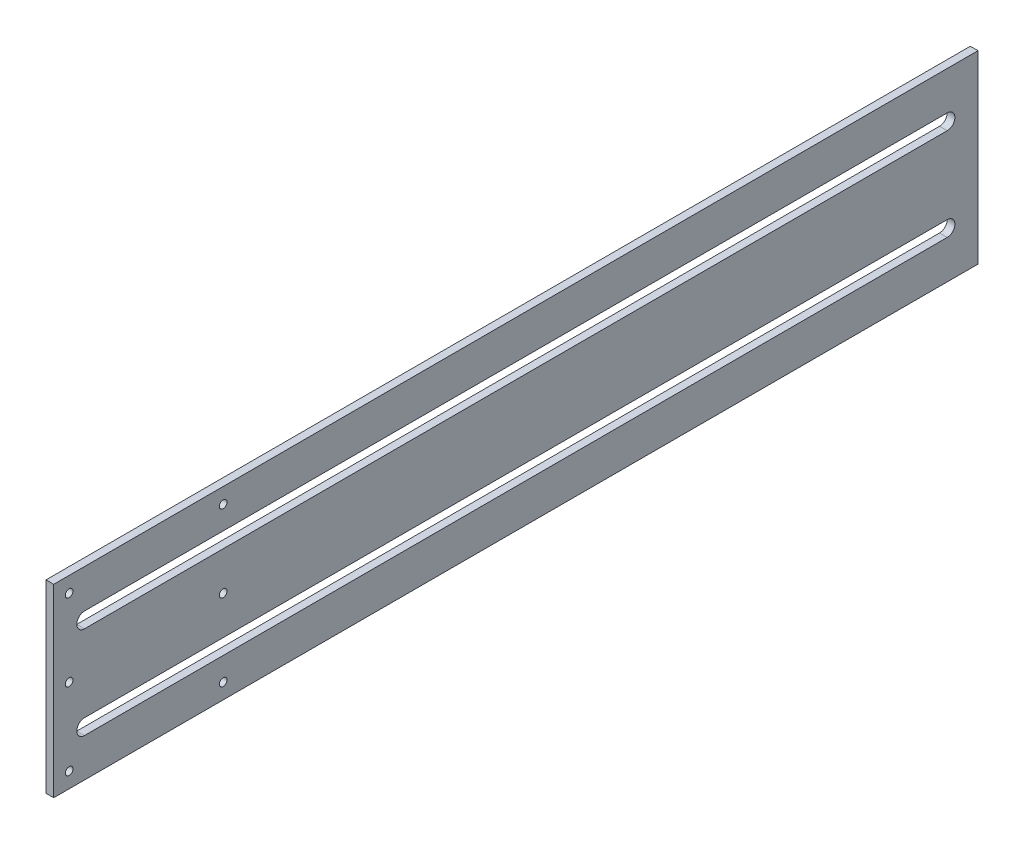
SolidWorks part; units mm, degrees
ref_plane "Front Plane" through (0, 0, 0) normal (0, 0, 1) x (1, 0, 0)
ref_plane "Top Plane" through (0, 0, 0) normal (0, 1, 0) x (1, 0, 0)
ref_plane "Right Plane" through (0, 0, 0) normal (1, 0, 0) x (0, 0, -1)
sketch "Sketch1" plane through (0, 0, 0) normal (1, 0, 0) x (0, 0, -1)
  line L1 (-190.5, -38.1) -> (190.5, -38.1)
  line L2 (-190.5, -38.1) -> (-190.5, 38.1)
  line L3 (-190.5, 38.1) -> (190.5, 38.1)
  line L4 (190.5, -38.1) -> (190.5, 38.1)
  line L5 (-190.5, -38.1) -> (190.5, 38.1) construction
  line L6 (-190.5, 38.1) -> (190.5, -38.1) construction
  point P0 (0, 0)
  dimension "D1" = 381
  dimension "D2" = 76.2
extrude "Outer Cut" add sketch "Sketch1" along normal mid plane 3.175
sketch "Sketch2" plane through (1.5875, 0, 0) normal (1, 0, 0) x (0, 0, -1)
  line L0 (-177.8, 19.05) -> (177.8, 19.05) construction
  line L1 (-177.8, 22.225) -> (177.8, 22.225)
  line L2 (-177.8, 15.875) -> (177.8, 15.875)
  line L3 (-190.5, 0) -> (190.5, 0) construction
  line L6 (190.5, -38.1) -> (190.5, 38.1) construction
  line L7 (-190.5, 38.1) -> (-190.5, -38.1) construction
  line L8 (-177.8, -19.05) -> (177.8, -19.05) construction
  line L9 (-177.8, -22.225) -> (177.8, -22.225)
  line L10 (-177.8, -15.875) -> (177.8, -15.875)
  arc A0 (-177.8, 22.225) -> (-177.8, 15.875) centre (-177.8, 19.05) ccw
  arc A1 (177.8, 15.875) -> (177.8, 22.225) centre (177.8, 19.05) ccw
  arc A2 (-177.8, -22.225) -> (-177.8, -15.875) centre (-177.8, -19.05) cw
  arc A3 (177.8, -15.875) -> (177.8, -22.225) centre (177.8, -19.05) cw
  point P2 (0, 19.05)
  point P18 (0, -19.05)
  dimension "D1" = 6.35
  dimension "D2" = 38.1
  dimension "D3" = 12.7
  dimension "D4" = 12.7
extrude "Slots" cut sketch "Sketch2" against normal through all
sketch "Sketch3" plane through (1.5875, 0, 0) normal (1, 0, 0) x (0, 0, -1)
  line L0 (-184.15, 31.75) -> (-120.65, 31.75) construction
  line L1 (190.5, 38.1) -> (-190.5, 38.1) construction
  line L2 (-190.5, 38.1) -> (-190.5, -38.1) construction
  line L3 (0, 0) -> (-190.5, 0) construction
  circle A0 centre (-184.15, 31.75) radius 1.5875
  circle A1 centre (-120.65, 31.75) radius 1.5875
  circle A2 centre (-120.65, -31.75) radius 1.5875
  circle A3 centre (-184.15, -31.75) radius 1.5875
  circle A4 centre (-184.15, 0) radius 1.5875
  circle A5 centre (-120.65, 0) radius 1.5875
  point P20 (0, 0)
  point P21 (0, 0)
  point P22 (0, 0)
  dimension "D1" = 3.175
  dimension "D3" = 63.5
  dimension "D4" = 6.35
  dimension "D5" = 6.35
extrude "Mount Holes" cut sketch "Sketch3" against normal through all
